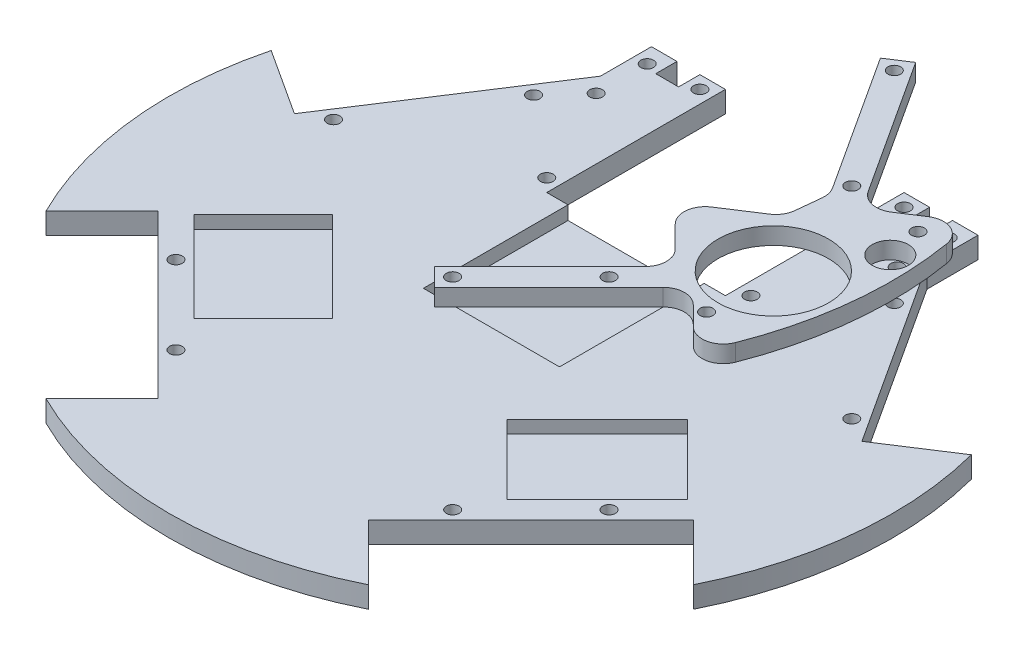
SolidWorks part; units mm, degrees
ref_plane "Front" through (0, 0, 0) normal (0, 0, 1) x (1, 0, 0)
ref_plane "Top" through (0, 0, 0) normal (0, 1, 0) x (1, 0, 0)
ref_plane "Right" through (0, 0, 0) normal (1, 0, 0) x (0, 0, -1)
sketch "Sketch1" plane through (0, 0, 0) normal (0, 1, 0) x (1, 0, 0)
  line L0 (0, 0) -> (85, 0)
  line L1 (0, 85) -> (0, 0)
  line L2 (-85, 0) -> (0, 0)
  line L3 (0, -85) -> (0, 0)
  line L4 (0, 0) -> (60.1041, -60.1041)
  line L5 (0, 0) -> (-60.1041, -60.1041)
  line L6 (0, 0) -> (71.287, 46.2943)
  line L7 (0, 0) -> (-71.287, 46.2943)
  line L8 (54.5179, 65.2134) -> (38.3816, 54.7344)
  line L9 (38.3816, 54.7344) -> (66.7028, 11.1235)
  line L10 (66.7028, 11.1235) -> (82.3002, 21.2526)
  line L11 (76.0831, -37.8993) -> (62.9325, -24.7487)
  line L12 (62.9325, -24.7487) -> (24.7487, -62.9325)
  line L13 (24.7487, -62.9325) -> (37.8993, -76.0831)
  line L14 (-37.8993, -76.0831) -> (-24.7487, -62.9325)
  line L15 (-24.7487, -62.9325) -> (-62.9325, -24.7487)
  line L16 (-62.9325, -24.7487) -> (-76.0831, -37.8993)
  line L17 (-82.3002, 21.2526) -> (-66.7028, 11.1235)
  line L18 (-66.7028, 11.1235) -> (-38.3816, 54.7344)
  line L19 (-38.3816, 54.7344) -> (-54.5179, 65.2134)
  line L20 (-54.5179, 65.2134) -> (2.4596, 65.2134)
  line L21 (2.4596, 65.2134) -> (54.5179, 65.2134)
  line L22 (-38.3816, 54.7344) -> (0, 54.7344)
  line L23 (0, 54.7344) -> (38.3816, 54.7344)
  line L24 (38.3816, 54.7344) -> (38.3816, 75.841)
  line L25 (-38.3816, 75.841) -> (0, 75.841)
  line L26 (-38.3816, 75.841) -> (-38.3816, 54.7344)
  line L27 (0, 75.841) -> (38.3816, 75.841)
  circle A0 centre (0, 0) radius 85
  dimension "D1" = 170
  dimension "D2" = 33
  dimension "D3" = 33
  dimension "D4" = 45
  dimension "D5" = 23
  dimension "D6" = 23
  dimension "D7" = 23
  dimension "D8" = 23
  dimension "D9" = 25
  dimension "D10" = 27
  dimension "D11" = 27
  dimension "D12" = 27
  dimension "D13" = 27
  dimension "D14" = 27
  dimension "D15" = 27
  dimension "D16" = 25
sketch "Sketch2" plane through (0, 0, 0) normal (0, 1, 0) x (1, 0, 0)
  line L0 (82.3002, 21.2526) -> (66.7028, 11.1235)
  line L1 (66.7028, 11.1235) -> (38.3816, 54.7344)
  line L2 (76.0831, -37.8993) -> (62.9325, -24.7487)
  line L3 (62.9325, -24.7487) -> (24.7487, -62.9325)
  line L4 (24.7487, -62.9325) -> (37.8993, -76.0831)
  line L5 (-37.8993, -76.0831) -> (-24.7487, -62.9325)
  line L6 (-24.7487, -62.9325) -> (-62.9325, -24.7487)
  line L7 (-62.9325, -24.7487) -> (-76.0831, -37.8993)
  line L8 (-82.3002, 21.2526) -> (-66.7028, 11.1235)
  line L9 (-66.7028, 11.1235) -> (-38.3816, 54.7344)
  line L10 (-38.3816, 54.7344) -> (-38.3816, 66.7344)
  line L11 (-38.3816, 75.841) -> (-38.3816, 54.7344) construction
  line L12 (-38.3816, 66.7344) -> (38.3816, 66.7344)
  line L13 (38.3816, 54.7344) -> (38.3816, 75.841) construction
  line L14 (38.3816, 66.7344) -> (38.3816, 54.7344)
  arc A0 (82.3002, 21.2526) -> (76.0831, -37.8993) centre (0, 0) cw
  arc A1 (37.8993, -76.0831) -> (-37.8993, -76.0831) centre (0, 0) cw
  arc A2 (-76.0831, -37.8993) -> (-82.3002, 21.2526) centre (0, 0) cw
  dimension "D1" = 12
extrude "Extrude1" add sketch "Sketch2" against normal blind 5
sketch "Sketch3" plane through (0, 0, 0) normal (0, 1, 0) x (1, 0, 0)
  line L0 (-21, 71.7344) -> (-21, 24.7344)
  line L1 (-21, 24.7344) -> (21, 24.7344)
  line L2 (21, 24.7344) -> (21, 71.7344)
  line L3 (21, 71.7344) -> (-21, 71.7344)
  line L4 (38.3816, 66.7344) -> (-38.3816, 66.7344) construction
  dimension "D1" = 21
  dimension "D2" = 21
  dimension "D3" = 42
  dimension "D4" = 5
extrude "Extrude2" cut sketch "Sketch3" against normal up to surface (5 mm away) up to face at (0, -5, 6.6049)
sketch "Sketch4" plane through (0, 0, 0) normal (0, 1, 0) x (-1, 0, 0)
  line L0 (16, 9.2656) -> (16, -30.7344)
  line L2 (16, 9.2656) -> (-16, 9.2656)
  line L3 (16, -30.7344) -> (-16, -30.7344)
  line L4 (-16, -30.7344) -> (-16, 9.2656)
  line L5 (21, -24.7344) -> (-21, -24.7344) construction
  dimension "D1" = 32
  dimension "D2" = 16
  dimension "D3" = 34
  dimension "D4" = 40
extrude "Extrude3" cut sketch "Sketch4" against normal blind 3.2
sketch "Sketch5" plane through (0, 0, 0) normal (0, 1, 0) x (1, 0, 0)
  line L0 (36.7696, -42.4264) -> (57.9828, -21.2132)
  line L1 (57.9828, -21.2132) -> (41.7193, -4.9497)
  line L2 (41.7193, -4.9497) -> (20.5061, -26.163)
  line L3 (20.5061, -26.163) -> (36.7696, -42.4264)
  line L4 (24.7487, -62.9325) -> (62.9325, -24.7487) construction
  line L6 (62.9325, -24.7487) -> (76.0831, -37.8993) construction
  dimension "D1" = 6
  dimension "D2" = 23
  dimension "D3" = 30
  dimension "D4" = 1
extrude "Extrude4" cut sketch "Sketch5" against normal blind 3
mirror "Mirror1" about plane through (0, 0, 0) normal (1, 0, 0) of "Extrude4"
sketch "Sketch6" plane through (0, 0, 0) normal (0, 1, 0) x (1, 0, 0)
  line L0 (0, 0) -> (71.287, 46.2943) construction
  line L1 (38.3816, 54.7344) -> (66.7028, 11.1235) construction
  line L2 (62.9325, -24.7487) -> (24.7487, -62.9325) construction
  line L3 (0, 0) -> (60.1041, -60.1041) construction
  circle A0 centre (42.4013, 43.0364) radius 1.5
  circle A1 centre (60.919, 14.5216) radius 1.5
  circle A2 centre (50.9117, -32.5269) radius 1.5
  circle A3 centre (32.5269, -50.9117) radius 1.5
  dimension "D1" = 3
  dimension "D2" = 3
  dimension "D3" = 3
  dimension "D4" = 3
  dimension "D6" = 3
  dimension "D8" = 3
  dimension "D9" = 3
  dimension "D10" = 13
  dimension "D11" = 13
  dimension "D12" = 3
  dimension "D5" = 13
  dimension "D7" = 21
extrude "Extrude5" cut sketch "Sketch6" against normal up to surface (5 mm away) up to face at (0, -5, -3.863)
mirror "Mirror2" about plane through (0, 0, 0) normal (1, 0, 0) of "Extrude5"
sketch "Sketch7" plane through (0, 0, 0) normal (0, 1, 0) x (-1, 0, 0)
  line L0 (-38.3816, -66.7344) -> (-21, -66.7344) construction
  line L1 (-21, -24.7344) -> (-21, -66.7344) construction
  line L2 (-16, -24.7344) -> (-21, -24.7344) construction
  circle A0 centre (-24, -63.7344) radius 1.5
  circle A1 centre (-24, -27.7344) radius 1.5
  dimension "D2" = 3
  dimension "D3" = 3
  dimension "D4" = 3
  dimension "D5" = 3
  dimension "D6" = 3
  dimension "D1" = 3
extrude "Extrude6" cut sketch "Sketch7" against normal up to surface (5 mm away) up to face at (-50.9117, -5, 31.0269)
mirror "Mirror3" about plane through (0, 0, 0) normal (1, 0, 0) of "Extrude6"
sketch "Sketch8" plane through (0, 0, 0) normal (0, 1, 0) x (1, 0, 0)
  line L0 (32.3816, 68.7344) -> (32.3816, 61.7344)
  line L1 (32.3816, 61.7344) -> (27, 61.7344)
  line L2 (27, 61.7344) -> (27, 68.7344)
  line L3 (27, 68.7344) -> (32.3816, 68.7344)
  line L4 (38.3816, 54.7344) -> (38.3816, 66.7344) construction
  line L5 (38.3816, 66.7344) -> (21, 66.7344) construction
  circle A0 centre (24, 63.7344) radius 1.5 construction
  dimension "D1" = 6
  dimension "D2" = 3
  dimension "D3" = 2
  dimension "D4" = 5
extrude "Extrude7" cut sketch "Sketch8" against normal up to surface (5 mm away) up to face at (-24, -5, -65.2344)
mirror "Mirror4" about plane through (0, 0, 0) normal (1, 0, 0) of "Extrude7"
sketch "Sketch9" plane through (0, 0, 0) normal (0, 1, 0) x (1, 0, 0)
  line L0 (38.3816, 66.7344) -> (32.3816, 66.7344) construction
  line L1 (38.3816, 54.7344) -> (38.3816, 66.7344) construction
  circle A0 centre (35.3816, 62.7344) radius 1.5
  circle A1 centre (35.3816, 50.7344) radius 1.5
  dimension "D1" = 3
  dimension "D2" = 3
  dimension "D3" = 4
  dimension "D4" = 12
  dimension "D5" = 3
  dimension "D6" = 3
extrude "Extrude8" cut sketch "Sketch9" against normal up to surface (5 mm away) up to face at (-24, -5, -29.2344)
mirror "Mirror5" about plane through (0, 0, 0) normal (1, 0, 0) of "Extrude8"
ref_plane "Plane1" through (0, 43.4, 0) normal (0, 1, 0) x (-1, 0, 0)
sketch "Sketch10" plane through (0, 43.4, 0) normal (0, 1, 0) x (-1, 0, 0)
  line L0 (-43.2834, -47.1863) -> (-38.2513, -43.9185)
  line L1 (-66.7028, -11.1235) -> (-38.3816, -54.7344) construction
  line L2 (-38.2513, -43.9185) -> (-60.0369, -10.3717)
  line L3 (-43.2834, -47.1863) -> (-66.7028, -11.1235)
  line L4 (-66.7028, -11.1235) -> (-82.3002, -21.2526)
  line L5 (-76.0831, 37.8993) -> (-62.9325, 24.7487) construction
  line L6 (-60.0369, -10.3717) -> (-56.5685, 22.6274)
  line L7 (-24.7487, 62.9325) -> (-62.9325, 24.7487) construction
  line L8 (-32.5269, 55.1543) -> (-62.9325, 24.7487)
  line L9 (-62.9325, 24.7487) -> (-76.0831, 37.8993)
  line L11 (-28.2843, 50.9117) -> (-56.5685, 22.6274)
  line L12 (-28.2843, 50.9117) -> (-32.5269, 55.1543)
  arc A0 (-76.0831, 37.8993) -> (-82.3002, -21.2526) centre (0, 0) ccw construction
  circle A1 centre (-42.4013, -43.0364) radius 1.5 construction
  arc A2 (-82.3002, -21.2526) -> (-76.0831, 37.8993) centre (0, 0) cw
  circle A3 centre (0, 0) radius 85 construction
  circle A5 centre (-42.4013, -43.0364) radius 1.5
  circle A6 centre (-60.919, -14.5216) radius 1.5
  circle A7 centre (-50.9117, 32.5269) radius 1.5
  circle A8 centre (-32.5269, 50.9117) radius 1.5
  dimension "D4" = 85
  dimension "D13" = 3
  dimension "D14" = 3
  dimension "D15" = 3
  dimension "D16" = 3
  dimension "D2" = 6
  dimension "D1" = 3
  dimension "D6" = 3
  dimension "D7" = 6
  dimension "D8" = 40
  dimension "D9" = 40
extrude "Extrude9" add sketch "Sketch10" along normal blind 4
sketch "Sketch14" plane through (0, 47.4, 0) normal (0, 1, 0) x (1, 0, 0)
  circle A0 centre (79.5, 5) radius 4.25
  dimension "D1" = 8.5
  dimension "D2" = 79.5
  dimension "D3" = 5
extrude "Extrude12" cut sketch "Sketch14" against normal up to surface (4 mm away) up to face at (50.9117, 43.4, 34.0269)
fillet "Fillet3" [suppressed] radius 5
sketch "Sketch18" plane through (0, 47.4, 0) normal (0, 1, 0) x (1, 0, 0)
  circle A0 centre (78, 13) radius 1.5
  dimension "D1" = 3
  dimension "D2" = 13
  dimension "D3" = 78
extrude "Extrude16" cut sketch "Sketch18" against normal up to surface (4 mm away) up to face at (79.5, 43.4, -9.25)
sketch "Sketch20" plane through (0, 47.4, 0) normal (0, 1, 0) x (1, 0, 0)
  line L0 (0, 0) -> (0, -37.5582)
sketch "Sketch21" plane through (0, 47.4, 0) normal (0, 1, 0) x (1, 0, 0)
  line L0 (56.5685, -22.6274) -> (43.5455, -9.6044)
  line L1 (60.0369, 10.3717) -> (56.5685, -22.6274) construction
  line L2 (58.9916, 0.4265) -> (43.5455, -9.6044)
  line L3 (38.2513, 43.9185) -> (60.0369, 10.3717) construction
  line L4 (58.9916, 0.4265) -> (56.5685, -22.6274)
  line L6 (56.5685, -22.6274) -> (28.2843, -50.9117) construction
  dimension "D4" = 10
extrude "Extrude18" add sketch "Sketch21" against normal up to surface (4 mm away) up to face at (78, 43.4, -14.5)
fillet "Fillet5" radius 5 8 edges at (62.9325, 45.4, 24.7487) (76.0831, 45.4, 37.8993) (82.3002, 45.4, -21.2526) (66.7028, 45.4, -11.1235) (56.5685, 45.4, 22.6274) (43.5455, 45.4, 9.6044) (58.9916, 45.4, -0.4265) (60.0369, 45.4, -10.3717)
sketch "Sketch22" plane through (0, 47.4, 0) normal (0, 1, 0) x (1, 0, 0)
  line L0 (58.5315, 0.7084) -> (29.7325, 18.704)
  line L1 (38.2513, 43.9185) -> (59.0726, 11.8566) construction
  arc A0 (56.9915, -0.8724) -> (59.2409, 2.7983) centre (54.2683, 3.3209) ccw construction
  dimension "D1" = 155
sketch "Sketch23" plane through (0, 47.4, 0) normal (0, 1, 0) x (1, 0, 0)
  circle A0 centre (69.5, -28.2) radius 1.5
  circle A1 centre (78, 13) radius 1.5 construction
  dimension "D2" = 41.2
  dimension "D3" = 3
  dimension "D1" = 8.5
extrude "Extrude19" cut sketch "Sketch23" against normal up to surface (4 mm away) up to face at (78, 43.4, -14.5)
sketch "Sketch17" plane through (0, 47.4, 0) normal (0, 1, 0) x (1, 0, 0)
  circle A0 centre (69, -12) radius 13
  dimension "D3" = 26
  dimension "D1" = 12
  dimension "D2" = 69
extrude "Extrude20" cut sketch "Sketch17" against normal up to surface (4 mm away) up to face at (69.5, 43.4, 26.7)
